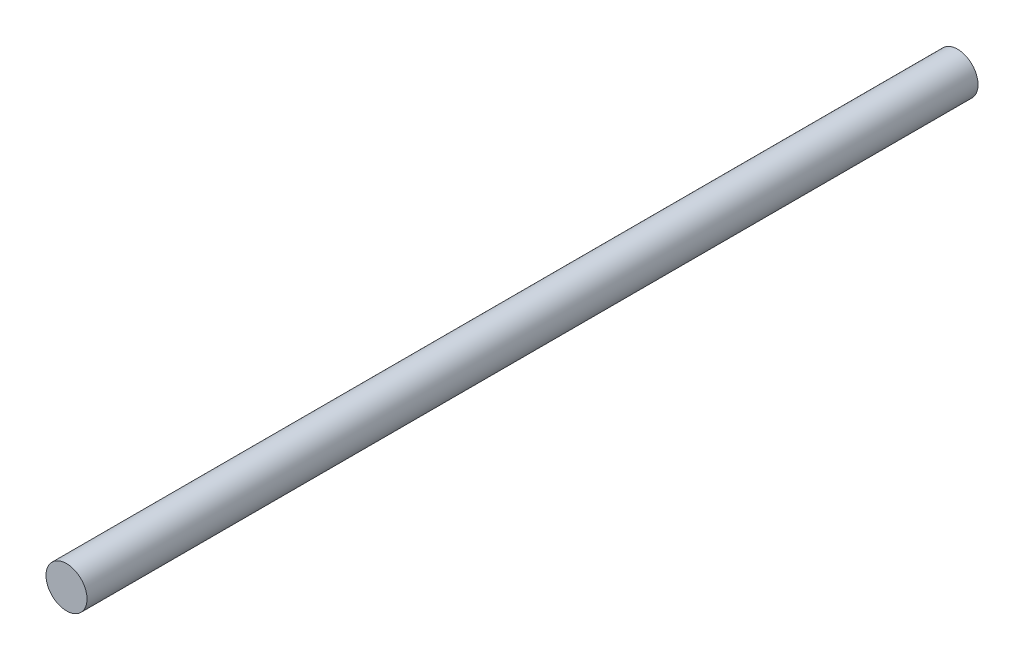
SolidWorks part; units mm, degrees
ref_plane "Front Plane" through (0, 0, 0) normal (0, 0, 1) x (1, 0, 0)
ref_plane "Top Plane" through (0, 0, 0) normal (0, 1, 0) x (1, 0, 0)
ref_plane "Right Plane" through (0, 0, 0) normal (1, 0, 0) x (0, 0, -1)
sketch "Sketch1" plane through (0, 0, 0) normal (0, 0, 1) x (1, 0, 0)
  circle A0 centre (0, 0) radius 4
  dimension "D1" = 8
extrude "Boss-Extrude1" add sketch "Sketch1" along normal blind 173.7
